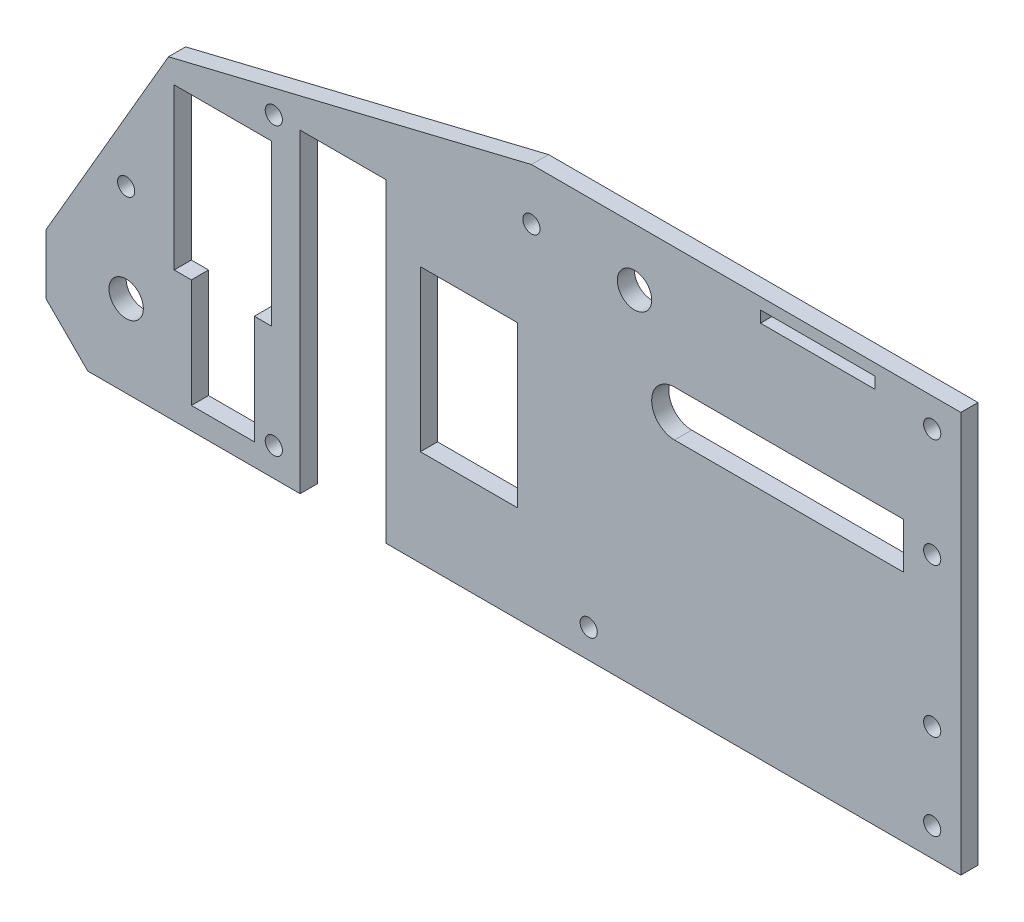
SolidWorks part; units mm, degrees
ref_plane "Front Plane" through (0, 0, 0) normal (0, 0, 1) x (1, 0, 0)
ref_plane "Top Plane" through (0, 0, 0) normal (0, 1, 0) x (1, 0, 0)
ref_plane "Right Plane" through (0, 0, 0) normal (1, 0, 0) x (0, 0, -1)
sketch "Sketch1" plane through (0, 0, 0) normal (0, 0, 1) x (1, 0, 0)
  line L0 (-211.6542, 23.1199) -> (-151.6542, 23.1199)
  line L1 (58.3458, 13.1199) -> (58.3458, -56.8801)
  line L2 (-121.6542, 33.1199) -> (-221.6542, 33.1199)
  line L3 (-221.6542, 33.1199) -> (-221.6542, -6.8801)
  line L4 (-191.6542, -56.8801) -> (58.3458, -56.8801)
  line L5 (-121.6542, 33.1199) -> (-91.6542, 13.1199)
  line L6 (-191.6542, -26.8801) -> (-191.6542, -56.8801)
  line L7 (-91.6542, 13.1199) -> (58.3458, 13.1199)
  line L8 (-211.6542, 3.1199) -> (-151.6542, 3.1199)
  line L9 (-151.6542, 3.1199) -> (-151.6542, 23.1199)
  line L10 (-211.6542, 23.1199) -> (-211.6542, 3.1199)
  line L12 (28.3458, 11.1199) -> (28.3458, 10.1199)
  line L13 (-221.6542, -6.8801) -> (-191.6542, -26.8801)
  line L14 (43.3458, 11.1199) -> (38.3458, 11.1199)
  line L15 (38.3458, 11.1199) -> (38.3458, 10.1199)
  line L16 (38.3458, 10.1199) -> (43.3458, 10.1199)
  line L17 (43.3458, 10.1199) -> (43.3458, 11.1199)
  line L18 (28.3458, 10.1199) -> (23.3458, 10.1199)
  line L19 (23.3458, 10.1199) -> (23.3458, 11.1199)
  line L20 (23.3458, 11.1199) -> (28.3458, 11.1199)
  circle A0 centre (53.3458, 7.9455) radius 1.25
  circle A1 centre (53.3458, -52.0545) radius 1.25
  circle A2 centre (25.5058, -18.3301) radius 0.75
extrude "Boss-Extrude2" add sketch "Sketch1" along normal blind 3
sketch "Sketch3" plane through (0, 0, 3) normal (0, 0, 1) x (1, 0, 0)
  circle A0 centre (1.3458, 3.1199) radius 1.25
extrude "Cut-Extrude2" cut sketch "Sketch3" against normal blind 3
sketch "Sketch15" plane through (0, 0, 3) normal (0, 0, 1) x (1, 0, 0)
  circle A0 centre (25.5058, -18.3301) radius 0.75
extrude "Boss-Extrude4" add sketch "Sketch15" against normal blind 3
sketch "Sketch20" plane through (0, 0, 3) normal (0, 0, 1) x (1, 0, 0)
  circle A0 centre (-16.6542, 4.1199) radius 1.25
sketch "Sketch23" plane through (0, 0, 3) normal (0, 0, 1) x (1, 0, 0)
  circle A0 centre (-93.5247, -7.5214) radius 0.75
extrude "Cut-Extrude21" cut sketch "Sketch23" against normal blind 10
sketch "Sketch24" plane through (0, 0, 3) normal (0, 0, 1) x (1, 0, 0)
  circle A0 centre (-107.3637, -9.6388) radius 0.75
extrude "Cut-Extrude22" cut sketch "Sketch24" against normal blind 10
sketch "Sketch25" plane through (0, 0, 3) normal (0, 0, 1) x (1, 0, 0)
  line L0 (58.3458, -56.8801) -> (-94.1442, -56.8801)
  line L1 (-191.6542, -56.8801) -> (58.3458, -56.8801) construction
sketch "Sketch26" plane through (0, 0, 3) normal (0, 0, 1) x (1, 0, 0)
  line L0 (-103.4442, -47.5801) -> (-103.4442, -42.5801)
  line L2 (-94.1442, -56.8801) -> (-191.6542, -56.8801)
  line L3 (-103.4442, -47.5801) -> (-94.1442, -56.8801)
  line L4 (58.3458, 13.1199) -> (-91.6542, 13.1199) construction
  line L5 (-191.6542, -56.8801) -> (-191.6542, -26.8801)
  line L6 (-80.0542, -2.2801) -> (-103.4442, -42.5801)
  line L7 (-80.0542, -2.2801) -> (-16.6542, 13.1199)
  line L8 (-191.6542, -26.8801) -> (-221.6542, -6.8801)
  line L9 (-221.6542, -6.8801) -> (-221.6542, 33.1199)
  line L10 (-221.6542, 33.1199) -> (-121.6542, 33.1199)
  line L11 (-121.6542, 33.1199) -> (-91.6542, 13.1199)
  line L12 (-91.6542, 13.1199) -> (-16.6542, 13.1199)
extrude "Cut-Extrude23" cut sketch "Sketch26" against normal blind 10
sketch "Sketch28" plane through (0, 0, 3) normal (0, 0, 1) x (1, 0, 0)
  line L0 (-36.0542, -12.0301) -> (-36.0542, -40.0301)
  line L1 (-36.0542, -12.0301) -> (-19.0542, -12.0301)
  line L2 (-36.0542, -40.0301) -> (-19.0542, -40.0301)
  line L3 (-19.0542, -40.0301) -> (-19.0542, -12.0301)
  line L4 (-79.0542, -6.0301) -> (-79.0542, -34.0301)
  line L5 (-79.0542, -6.0301) -> (-62.0542, -6.0301)
  line L6 (-79.0542, -34.0301) -> (-62.0542, -34.0301)
  line L7 (-62.0542, -34.0301) -> (-62.0542, -6.0301)
extrude "Cut-Extrude25" cut sketch "Sketch28" against normal blind 3
sketch "Sketch30" plane through (0, 0, 3) normal (0, 0, 1) x (1, 0, 0)
  circle A0 centre (-87.4442, -42.5801) radius 3
extrude "Cut-Extrude26" cut sketch "Sketch30" against normal blind 3
sketch "Sketch31" plane through (0, 0, 3) normal (0, 0, 1) x (1, 0, 0)
  line L1 (48.3458, -11.0545) -> (48.3458, -8.0545)
  line L2 (48.3458, -8.0545) -> (8.3458, -8.0545)
  line L4 (8.3458, -16.0545) -> (48.3458, -16.0545)
  line L5 (48.3458, -16.0545) -> (48.3458, -11.0545)
  arc A0 (8.3458, -8.0545) -> (8.3458, -16.0545) centre (8.3458, -12.0545) ccw
extrude "Cut-Extrude28" cut sketch "Sketch31" against normal blind 3
sketch "Sketch32" plane through (0, 0, 3) normal (0, 0, 1) x (1, 0, 0)
  circle A0 centre (1.3458, 3.1199) radius 3
extrude "Cut-Extrude29" cut sketch "Sketch32" against normal blind 3
sketch "Sketch33" plane through (0, 0, 3) normal (0, 0, 1) x (1, 0, 0)
  line L0 (28.3458, 11.1199) -> (38.3458, 11.1199)
  line L1 (38.3458, 11.1199) -> (38.3458, 10.1199)
  line L2 (38.3458, 10.1199) -> (28.3458, 10.1199)
  line L3 (28.3458, 10.1199) -> (28.3458, 11.1199)
extrude "Cut-Extrude30" cut sketch "Sketch33" against normal blind 3
sketch "Sketch35" plane through (0, 0, 3) normal (0, 0, 1) x (1, 0, 0)
  line L2 (-101.4442, -45.0801) -> (-101.4442, -39.1342)
  line L3 (-103.4442, -42.5801) -> (-80.0542, -2.2801) construction
  line L4 (-101.4442, -39.1342) -> (-103.4442, -42.5801)
  line L5 (-103.4442, -42.5801) -> (-103.4442, -47.5801)
  line L6 (-101.4442, -45.0801) -> (-101.4442, -49.5801)
  line L7 (-94.1442, -56.8801) -> (-103.4442, -47.5801) construction
  line L8 (-101.4442, -49.5801) -> (-103.4442, -47.5801)
extrude "Cut-Extrude32" cut sketch "Sketch35" against normal blind 3
sketch "Sketch36" plane through (0, 0, 3) normal (0, 0, 1) x (1, 0, 0)
  circle A0 centre (-61.6542, -1.8801) radius 1.5
extrude "Cut-Extrude33" cut sketch "Sketch36" against normal blind 3
sketch "Sketch37" plane through (0, 0, 3) normal (0, 0, 1) x (1, 0, 0)
  circle A0 centre (-87.4442, -25.5801) radius 1.5
extrude "Cut-Extrude34" cut sketch "Sketch37" against normal blind 3
sketch "Sketch39" plane through (0, 0, 3) normal (0, 0, 1) x (1, 0, 0)
  line L2 (-57.0542, -20.0301) -> (-57.0542, -56.8801)
  line L3 (58.3458, -56.8801) -> (-94.1442, -56.8801) construction
  line L4 (-57.0542, -56.8801) -> (-42.0542, -56.8801)
  line L5 (-42.0542, -56.8801) -> (-42.0542, -1.8801)
  line L6 (-42.0542, -1.8801) -> (-57.0542, -1.8801)
  line L7 (-57.0542, -1.8801) -> (-57.0542, -20.0301)
extrude "Cut-Extrude36" cut sketch "Sketch39" against normal blind 3
sketch "Sketch40" plane through (0, 0, 3) normal (0, 0, 1) x (1, 0, 0)
  circle A0 centre (53.3458, 7.9455) radius 1.25
extrude "Boss-Extrude5" add sketch "Sketch40" against normal blind 3
sketch "Sketch41" plane through (0, 0, 3) normal (0, 0, 1) x (1, 0, 0)
  circle A0 centre (53.3458, -52.0545) radius 1.25
extrude "Boss-Extrude6" add sketch "Sketch41" against normal blind 3
sketch "Sketch42" plane through (0, 0, 3) normal (0, 0, 1) x (1, 0, 0)
  circle A0 centre (53.3458, -51.8801) radius 1.5
extrude "Cut-Extrude37" cut sketch "Sketch42" against normal blind 3
sketch "Sketch43" plane through (0, 0, 3) normal (0, 0, 1) x (1, 0, 0)
  circle A0 centre (-6.6542, -51.8801) radius 1.5
extrude "Cut-Extrude38" cut sketch "Sketch43" against normal blind 3
sketch "Sketch44" plane through (0, 0, 3) normal (0, 0, 1) x (1, 0, 0)
  circle A0 centre (-61.6542, -51.8801) radius 1.5
extrude "Cut-Extrude39" cut sketch "Sketch44" against normal blind 3
sketch "Sketch45" plane through (0, 0, 3) normal (0, 0, 1) x (1, 0, 0)
  circle A0 centre (53.3458, 8.1199) radius 1.5
  circle A1 centre (53.3458, -10.8801) radius 1.5
  circle A2 centre (53.3458, -36.8801) radius 1.5
extrude "Cut-Extrude40" cut sketch "Sketch45" against normal blind 3
sketch "Sketch46" plane through (0, 0, 3) normal (0, 0, 1) x (1, 0, 0)
  circle A0 centre (-16.6542, 4.1199) radius 1.5
extrude "Cut-Extrude41" cut sketch "Sketch46" against normal blind 3
sketch "Sketch47" plane through (0, 0, 3) normal (0, 0, 1) x (1, 0, 0)
  line L0 (23.3458, 10.1199) -> (23.3458, 9.1199)
  line L1 (23.3458, 9.1199) -> (43.3458, 9.1199)
  line L2 (43.3458, 9.1199) -> (43.3458, 10.1199)
  line L3 (43.3458, 10.1199) -> (23.3458, 10.1199)
extrude "Cut-Extrude42" cut sketch "Sketch47" against normal blind 3
sketch "Sketch48" plane through (0, 0, 3) normal (0, 0, 1) x (1, 0, 0)
  line L0 (-76.0542, -34.0301) -> (-76.0542, -53.0301)
  line L1 (-79.0542, -34.0301) -> (-62.0542, -34.0301) construction
  line L2 (-76.0542, -53.0301) -> (-65.0542, -53.0301)
  line L4 (-65.0542, -53.0301) -> (-65.0542, -34.0301)
  line L6 (-65.0542, -34.0301) -> (-76.0542, -34.0301)
extrude "Cut-Extrude44" cut sketch "Sketch48" against normal blind 10
